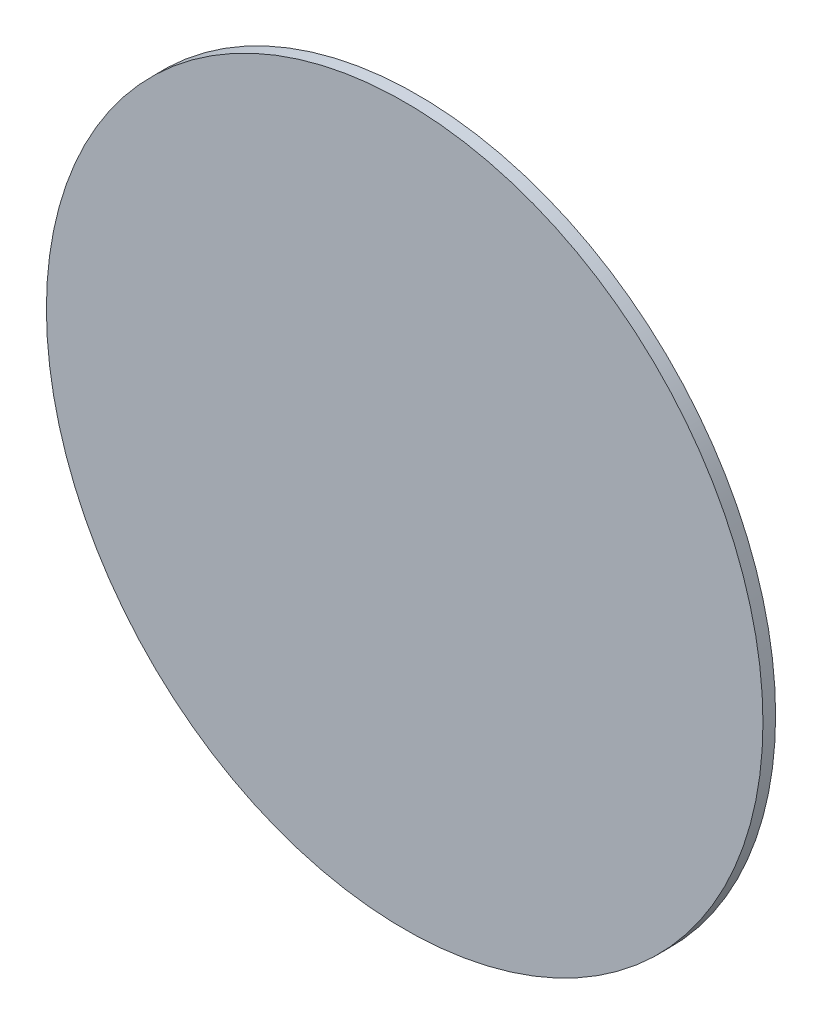
SolidWorks part; units mm, degrees
material "6061-T6 (SS)"
ref_plane "Front Plane" through (0, 0, 0) normal (0, 0, 1) x (1, 0, 0)
ref_plane "Top Plane" through (0, 0, 0) normal (0, 1, 0) x (1, 0, 0)
ref_plane "Right Plane" through (0, 0, 0) normal (1, 0, 0) x (0, 0, -1)
sketch "Sketch1" plane through (0, 0, 0) normal (0, 0, 1) x (1, 0, 0)
  circle A0 centre (0, 0) radius 90 construction
  circle A1 centre (0, 0) radius 90
extrude "Boss-Extrude1" add sketch "Sketch1" along normal up to vertex (3.175 mm away)
